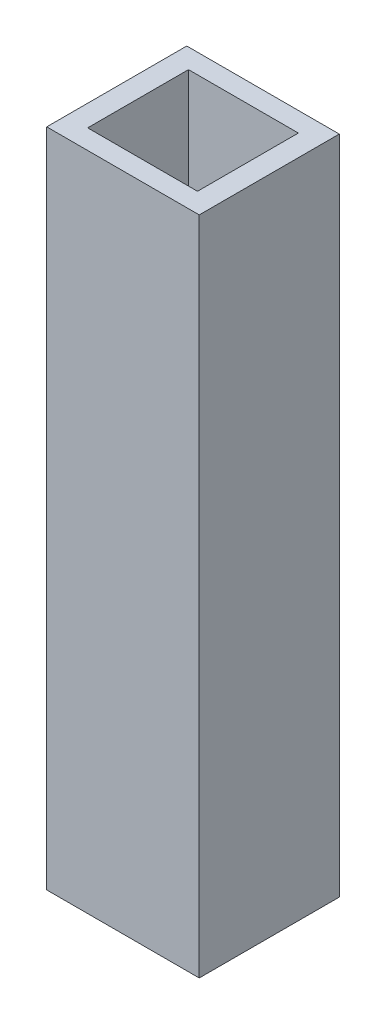
SolidWorks part; units mm, degrees
ref_plane "Alzado" through (0, 0, 0) normal (0, 0, 1) x (1, 0, 0)
ref_plane "Planta" through (0, 0, 0) normal (0, 1, 0) x (1, 0, 0)
ref_plane "Vista lateral" through (0, 0, 0) normal (1, 0, 0) x (0, 0, -1)
sketch "Croquis1" plane through (0, 0, 0) normal (0, 1, 0) x (1, 0, 0)
  line L1 (-15, 13.7727) -> (15, 13.7727)
  line L2 (-15, 13.7727) -> (-15, -13.7727)
  line L3 (-15, -13.7727) -> (15, -13.7727)
  line L4 (15, 13.7727) -> (15, -13.7727)
  line L5 (-15, 13.7727) -> (15, -13.7727) construction
  line L6 (-15, -13.7727) -> (15, 13.7727) construction
  line L7 (-10.8042, 9.9202) -> (10.8042, 9.9202)
  line L8 (-10.8042, 9.9202) -> (-10.8042, -9.9202)
  line L9 (-10.8042, -9.9202) -> (10.8042, -9.9202)
  line L10 (10.8042, 9.9202) -> (10.8042, -9.9202)
  line L11 (-10.8042, 9.9202) -> (10.8042, -9.9202) construction
  line L12 (-10.8042, -9.9202) -> (10.8042, 9.9202) construction
  point P0 (0, 0)
  point P6 (0, 0)
  dimension "D1" = 30
extrude "Saliente-Extruir1" add sketch "Croquis1" along normal blind 130
